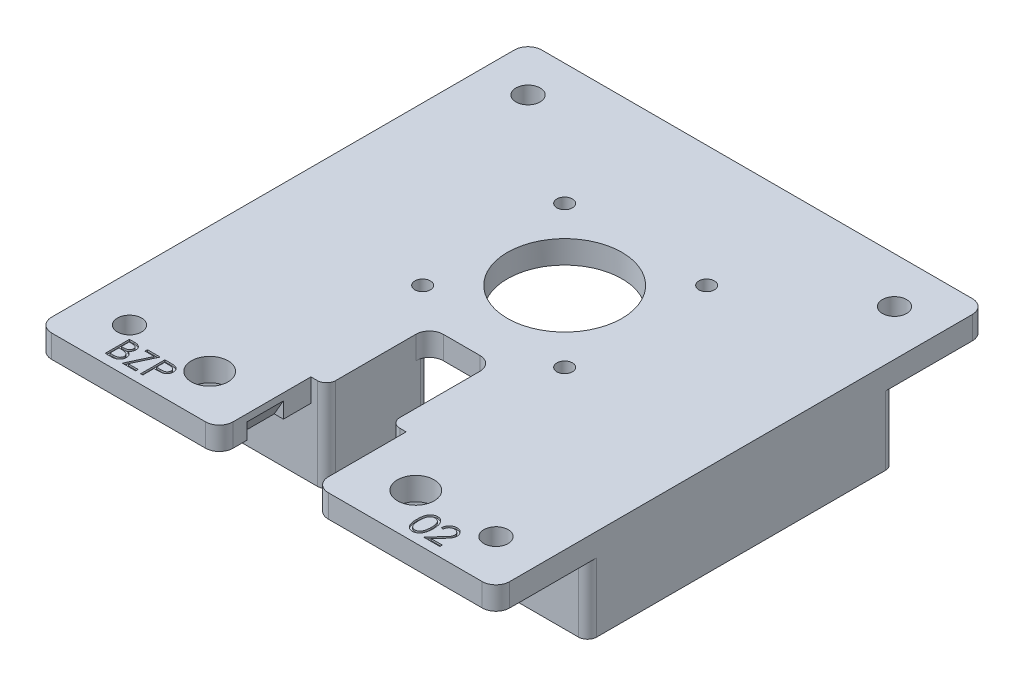
SolidWorks part; units mm, degrees
ref_plane "Front" through (0, 0, 0) normal (0, 0, 1) x (1, 0, 0)
ref_plane "Top" through (0, 0, 0) normal (0, 1, 0) x (1, 0, 0)
ref_plane "Right" through (0, 0, 0) normal (1, 0, 0) x (0, 0, -1)
sketch "Sketch2" plane through (0, 0, 0) normal (0, 1, 0) x (1, 0, 0)
  line L1 (0, 0) -> (100, 0)
  line L2 (0, 0) -> (0, 107)
  line L3 (0, 107) -> (100, 107)
  line L4 (100, 0) -> (100, 107)
  dimension "D1" = 107
  dimension "D2" = 100
extrude "Boss-Extrude1" add sketch "Sketch2" along normal blind 5
sketch "Sketch3" plane through (0, 5, 0) normal (0, 1, 0) x (1, 0, 0)
  line L0 (39.6, 0) -> (39.6, 20)
  line L1 (0, 0) -> (100, 0) construction
  line L2 (39.6, 20) -> (43, 20)
  line L3 (43, 20) -> (43, 42.5)
  line L4 (43, 42.5) -> (57, 42.5)
  line L5 (57, 42.5) -> (57, 20)
  line L6 (57, 20) -> (60.4, 20)
  line L7 (60.4, 20) -> (60.4, 0)
  line L8 (60.4, 0) -> (39.6, 0)
  line L9 (50, 107) -> (50, 65) construction
  line L10 (100, 107) -> (0, 107) construction
  line L11 (43, 42.5) -> (27.5, 42.5) construction
  line L12 (27.5, 87.5) -> (72.5, 87.5) construction
  line L13 (27.5, 87.5) -> (27.5, 42.5) construction
  line L14 (34.5, 49.5) -> (65.5, 49.5) construction
  line L15 (34.5, 49.5) -> (34.5, 80.5) construction
  line L16 (34.5, 80.5) -> (65.5, 80.5) construction
  line L17 (65.5, 49.5) -> (65.5, 80.5) construction
  line L18 (34.5, 49.5) -> (65.5, 80.5) construction
  line L19 (34.5, 80.5) -> (65.5, 49.5) construction
  line L20 (27.5, 42.5) -> (72.5, 42.5) construction
  line L21 (72.5, 87.5) -> (72.5, 42.5) construction
  line L22 (27.5, 87.5) -> (72.5, 42.5) construction
  line L23 (27.5, 42.5) -> (72.5, 87.5) construction
  line L24 (57, 42.5) -> (72.5, 42.5) construction
  line L25 (40, 10) -> (27.5, 10) construction
  line L26 (75, 47) -> (25, 47) construction
  line L27 (75, 47) -> (75, 83) construction
  line L28 (75, 83) -> (25, 83) construction
  line L29 (25, 47) -> (25, 83) construction
  line L30 (75, 47) -> (25, 83) construction
  line L31 (75, 83) -> (25, 47) construction
  line L32 (50, 65) -> (50, 10) construction
  line L33 (40, 0) -> (60, 0) construction
  line L34 (40, 0) -> (40, 20) construction
  line L35 (40, 20) -> (60, 20) construction
  line L36 (60, 0) -> (60, 20) construction
  line L37 (40, 0) -> (60, 20) construction
  line L38 (40, 20) -> (60, 0) construction
  circle A0 centre (50, 65) radius 12.5
  circle A1 centre (65.5, 49.5) radius 1.7
  circle A2 centre (34.5, 49.5) radius 1.7
  circle A3 centre (65.5, 80.5) radius 1.7
  circle A4 centre (34.5, 80.5) radius 1.7
  circle A5 centre (25, 83) radius 1.7 construction
  circle A6 centre (25, 47) radius 1.7 construction
  circle A7 centre (75, 47) radius 1.7 construction
  circle A8 centre (75, 83) radius 1.7 construction
  circle A9 centre (27.5, 10) radius 4
  circle A10 centre (72.5, 10) radius 4
  point P11 (50, 0)
  point P12 (50, 0)
  point P42 (50, 10)
  dimension "D4" = 25
  dimension "D6" = 3.4
  dimension "D10" = 3.4
  dimension "D12" = 8
  dimension "D2" = 14
  dimension "D3" = 20.8
  dimension "D5" = 31
  dimension "D7" = 42
  dimension "D8" = 50
  dimension "D9" = 36
  dimension "D11" = 45
  dimension "D13" = 20
  dimension "D14" = 12.5
  dimension "D15" = 20
extrude "Cut-Extrude1" cut sketch "Sketch3" against normal through all both and the other way through all
hole_wizard "M5 Clearance Hole1" positions "Sketch6" profile "Sketch5" hole size "M5" standard "ANSI Metric" end condition through all
sketch "Sketch6" plane through (0, 5, 0) normal (0, 1, 0) x (1, 0, 0)
  line L0 (0, 97) -> (100, 97) construction
  line L1 (0, 107) -> (0, 0) construction
  line L2 (100, 0) -> (100, 107) construction
  line L5 (10, 107) -> (10, 0) construction
  line L6 (100, 107) -> (0, 107) construction
  line L7 (0, 0) -> (39.6, 0) construction
  line L10 (90, 107) -> (90, 0) construction
  line L11 (60.4, 0) -> (100, 0) construction
  line L14 (0, 10) -> (100, 10) construction
  point P0 (10, 97)
  point P2 (10, 10)
  point P4 (90, 10)
  point P6 (90, 97)
  dimension "D1" = 10
  dimension "D2" = 10
  dimension "D3" = 10
  dimension "D4" = 10
sketch "Sketch5" plane through (10, 5, -97) normal (1, 0, 0) x (0, 0, 1)
  line L0 (0, 0) -> (0, 5)
  line L1 (0, 5) -> (2.65, 5)
  line L2 (2.65, 5) -> (2.65, 0)
  line L5 (2.65, 0) -> (0, 0)
  line L11 (0, -6.35) -> (0, 107.95) construction
  dimension "Thru Hole Dia." = 5.3
  dimension "Thru Hole Depth" = 5
fillet "Fillet1" radius 3 8 edges at (60.4, 2.5, 0) (39.6, 2.5, 0) (0, 2.5, -107) (100, 2.5, -107) (100, 2.5, 0) (0, 2.5, 0) (57, 2.5, -42.5) (43, 2.5, -42.5)
sketch "Sketch7" plane through (0, 0, 0) normal (0, -1, 0) x (1, 0, 0)
  line L0 (57, -20) -> (100, -20)
  line L1 (100, -3) -> (100, -104) construction
  line L2 (100, -20) -> (100, -87)
  line L3 (100, -87) -> (84, -87)
  line L4 (84, -87) -> (84, -82)
  line L5 (84, -82) -> (95, -82)
  line L6 (95, -82) -> (95, -25)
  line L7 (95, -25) -> (57, -25) construction
  line L8 (57, -25) -> (57, -20)
  line L9 (63.4, 0) -> (97, 0) construction
  line L10 (57, -20) -> (57, -39.5) construction
  line L11 (97, -107) -> (3, -107) construction
  line L12 (50, -107) -> (50, -46.1063) construction
  line L13 (43, -25) -> (43, -20)
  line L14 (5, -25) -> (43, -25) construction
  line L15 (5, -82) -> (5, -25)
  line L16 (16, -82) -> (5, -82)
  line L17 (16, -87) -> (16, -82)
  line L18 (0, -87) -> (16, -87)
  line L19 (0, -20) -> (0, -87)
  line L20 (43, -20) -> (0, -20)
  line L21 (57, -25) -> (57, -42.5)
  line L23 (57, -42.5) -> (62, -42.5)
  line L25 (62, -42.5) -> (62, -25)
  line L26 (62, -25) -> (95, -25)
  line L27 (38, -25) -> (5, -25)
  line L28 (38, -42.5) -> (38, -25)
  line L29 (43, -25) -> (43, -42.5)
  line L31 (43, -42.5) -> (38, -42.5)
  line L32 (54, -42.5) -> (46, -42.5) construction
  dimension "D1" = 20
  dimension "D2" = 20
  dimension "D3" = 16
  dimension "D4" = 5
  dimension "D5" = 5
extrude "Boss-Extrude2" add sketch "Sketch7" along normal blind 15
fillet "Fillet3" radius 3 6 edges at (5, -7.5, -82) (95, -7.5, -82) (5, -7.5, -25) (38, -7.5, -25) (95, -7.5, -25) (62, -7.5, -25)
fillet "Fillet4" radius 2 14 edges at (100, -7.5, -87) (100, -7.5, -20) (43, -5, -20) (57, -5, -20) (84, -7.5, -87) (84, -7.5, -82) (0, -7.5, -20) (0, -7.5, -87) (16, -7.5, -87) (16, -7.5, -82) (38, -7.5, -42.5) (62, -7.5, -42.5) (57, -7.5, -42.5) (43, -7.5, -42.5)
ref_plane "Plane1" through (0, 0, -10) normal (0, 0, 1) x (1, 0, 0)
sketch "Sketch9" plane through (0, 0, -10) normal (0, 0, 1) x (1, 0, 0)
  line L0 (39.6, 0) -> (39.6, 3.4641)
  line L2 (39.6, 0) -> (39.6, 5) construction
  line L3 (39.6, 3.4641) -> (37.6, 0)
  line L4 (37.6, 0) -> (39.6, 0)
  line L5 (60.4, 0) -> (62.4, 0)
  line L6 (98, 0) -> (60.4, 0) construction
  line L7 (62.4, 0) -> (60.4, 3.4641)
  line L8 (60.4, 0) -> (60.4, 5) construction
  line L9 (60.4, 3.4641) -> (60.4, 0)
  dimension "D1" = 30
  dimension "D2" = 2
extrude "Cut-Extrude2" cut sketch "Sketch9" against normal blind 4 and the other way blind 4
sketch "Sketch10" plane through (0, 5, 0) normal (0, 1, 0) x (1, 0, 0)
  line L0 (0, 2) -> (36.1, 2) construction
  line L1 (0, 104) -> (0, 3) construction
  line L3 (3, 0) -> (36.6, 0) construction
  line L4 (39.6, 3) -> (39.6, 20) construction
  text T0 "BZP" font "Century Gothic" height in points 20
  point P4 (36.0886, 3)
  point P9 (0, 0)
  dimension "D1" = 2
  dimension "D2" = 3.5
extrude "Cut-Extrude3" cut sketch "Sketch10" against normal blind 0.4
sketch "Sketch11" plane through (0, 5, 0) normal (0, 1, 0) x (1, 0, 0)
  line L0 (63.9, 2) -> (100, 2) construction
  line L2 (100, 3) -> (100, 104) construction
  line L3 (63.4, 0) -> (97, 0) construction
  line L4 (60.4, 20) -> (60.4, 3) construction
  text T0 "02" font "Century Gothic" height in points 20
  point P2 (64.533, 2)
  point P9 (0, 0)
  dimension "D1" = 2
  dimension "D2" = 3.5
extrude "Cut-Extrude4" cut sketch "Sketch11" against normal blind 0.4
equation "\"D5@Sketch7\"=\"D4@Sketch7\""
